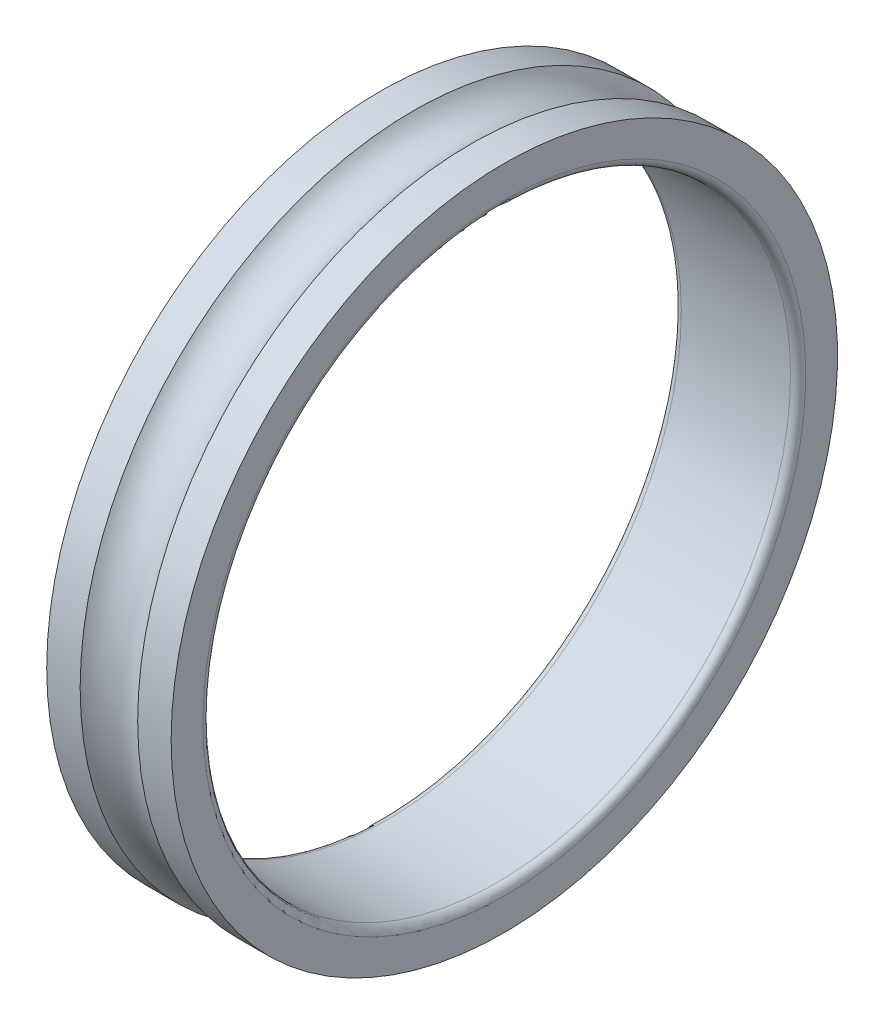
SolidWorks part; units mm, degrees
ref_plane "Piano frontale" through (0, 0, 0) normal (0, 0, 1) x (1, 0, 0)
ref_plane "Piano superiore" through (0, 0, 0) normal (0, 1, 0) x (1, 0, 0)
ref_plane "Piano destro" through (0, 0, 0) normal (1, 0, 0) x (0, 0, -1)
ref_plane "Piano1" through (0, 0, 0) normal (0, 0, 1) x (1, 0, 0)
sketch "Schizzo1" plane through (0, 0, 0) normal (0, 0, 1) x (1, 0, 0)
  line L0 (1.1, 42.5) -> (16.9, 42.5)
  line L1 (18, 43.6) -> (18, 48.2)
  line L2 (18, 48.2) -> (13.1615, 48.2)
  line L3 (4.8385, 48.2) -> (0, 48.2)
  line L4 (0, 48.2) -> (0, 43.6)
  line L5 (50, 0) -> (-50, 0) construction
  arc A0 (0, 43.6) -> (1.1, 42.5) centre (1.1, 43.6) ccw
  arc A1 (16.9, 42.5) -> (18, 43.6) centre (16.9, 43.6) ccw
  arc A2 (13.1615, 48.2) -> (4.8385, 48.2) centre (9, 51.25) cw
revolve "Rivoluzione1" add sketch "Schizzo1" angle 360 about L5
